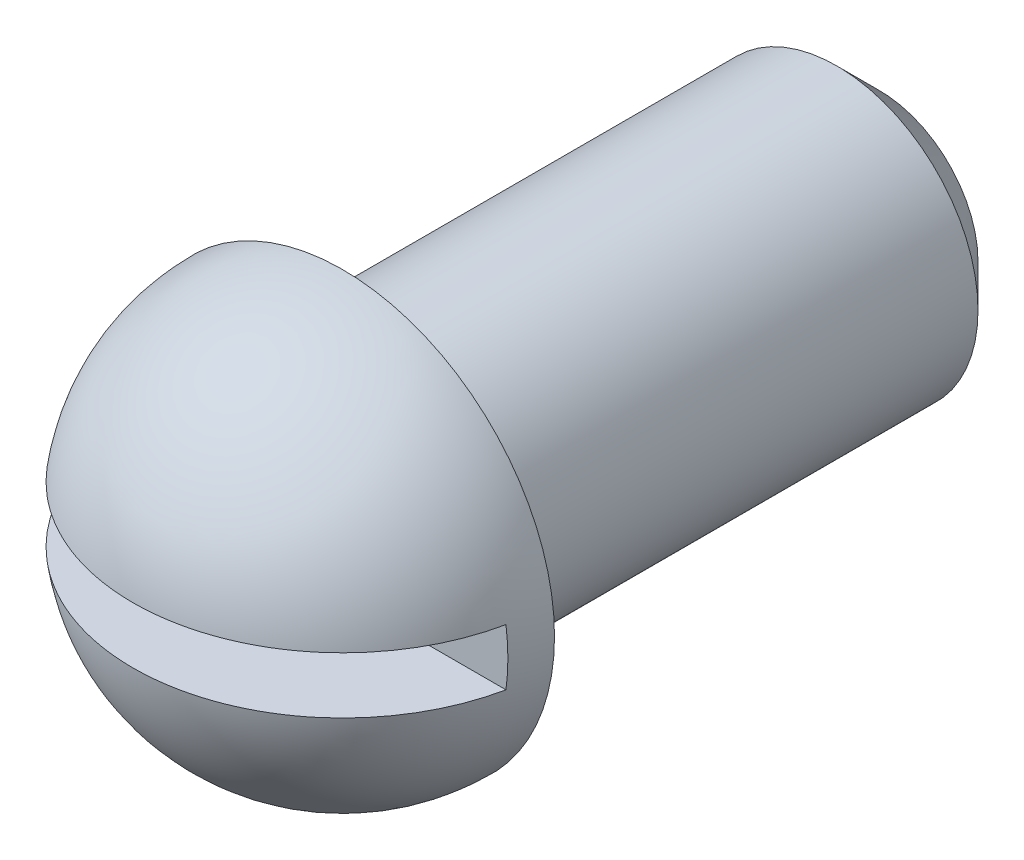
SolidWorks part; units mm, degrees
material "Alloy Steel"
ref_plane "Front Plane" through (0, 0, 0) normal (0, 0, 1) x (1, 0, 0)
ref_plane "Top Plane" through (0, 0, 0) normal (0, 1, 0) x (1, 0, 0)
ref_plane "Right Plane" through (0, 0, 0) normal (1, 0, 0) x (0, 0, -1)
sketch "Sketch1" plane through (0, 0, 0) normal (1, 0, 0) x (0, 0, -1)
  line L0 (-27.2853, 0) -> (27.2853, 0) construction
  line L1 (-19, 10) -> (-19, 15)
  line L4 (-19, 10) -> (19, 10)
  line L5 (19, 0) -> (19, 10)
  line L7 (19, 0) -> (-34, 0)
  arc A0 (-19, 15) -> (-34, 0) centre (-19, 0) ccw
  point P4 (0, 0)
  dimension "D4" = 30
  dimension "D1" = 10
  dimension "D2" = 38
revolve "Revolve1" add sketch "Sketch1" angle 360 about L0
sketch "Sketch2" plane through (0, 0, 0) normal (1, 0, 0) x (0, 0, -1)
  line L0 (-19, -15) -> (-19, 15) construction
  line L1 (-46, 2) -> (-22, 2)
  line L2 (-46, 2) -> (-46, -2)
  line L3 (-46, -2) -> (-22, -2)
  line L4 (-22, 2) -> (-22, -2)
  line L5 (-34, -2) -> (-34, 2) construction
  line L6 (-46, 0) -> (-22, 0) construction
  arc A0 (-19, 15) -> (-19, -15) centre (-19, 0) ccw construction
  point P0 (-34, 0)
  dimension "D1" = 4
  dimension "D2" = 3
extrude "Cut-Extrude1" cut sketch "Sketch2" against normal through all and the other way through all
chamfer "Chamfer1" distance 3 angle 45 1 edges at (10, 0, -19)
